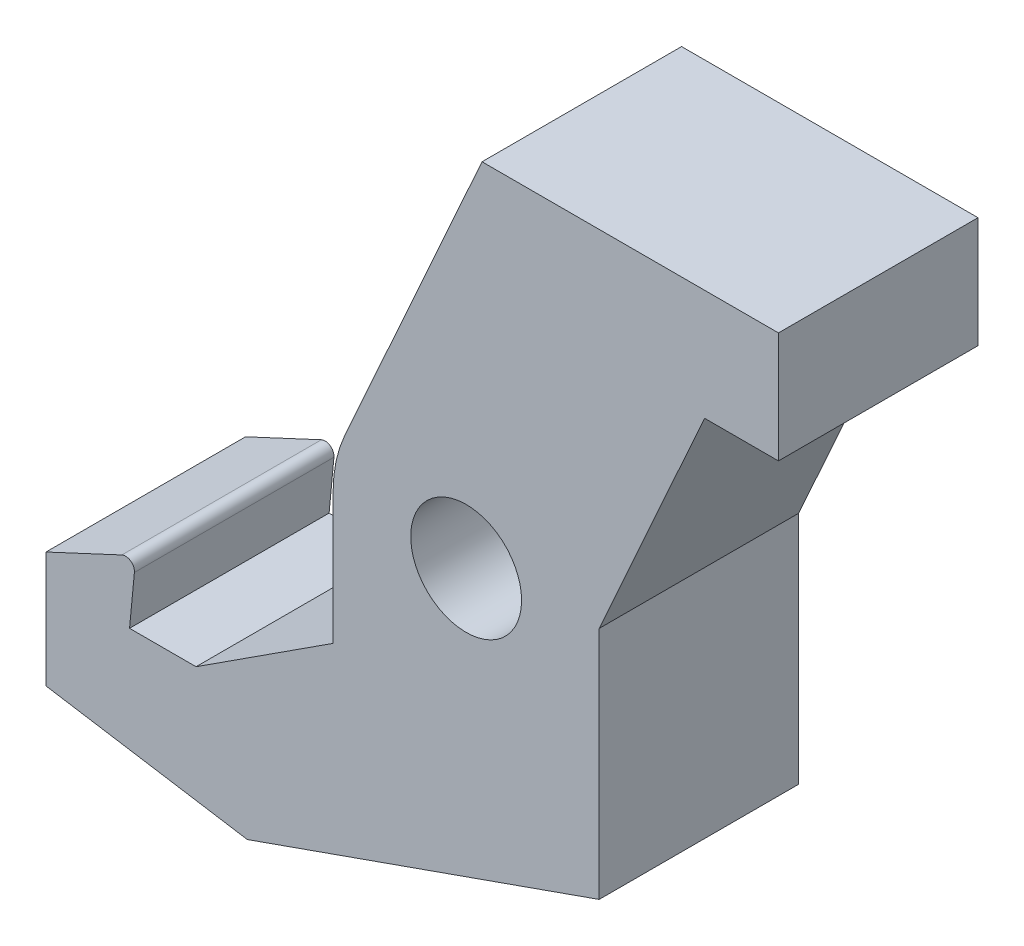
SolidWorks part; units mm, degrees
ref_plane "정면" through (0, 0, 0) normal (0, 0, 1) x (1, 0, 0)
ref_plane "윗면" through (0, 0, 0) normal (0, 1, 0) x (1, 0, 0)
ref_plane "우측면" through (0, 0, 0) normal (1, 0, 0) x (0, 0, -1)
sketch "스케치1" plane through (0, 0, 0) normal (0, 0, 1) x (1, 0, 0)
  line L0 (-6, 0) -> (-6, -5.9283)
  line L1 (-6, -5.9283) -> (-12.1815, -9.9309)
  line L2 (-12.1815, -9.9309) -> (-15.1815, -9.9309)
  line L3 (-15.1815, -9.9309) -> (-14.9625, -7.6405)
  line L4 (-15.5297, -7.2399) -> (-18.9497, -8.834)
  line L5 (-18.9497, -8.834) -> (-18.9497, -12.4044)
  line L6 (6, -9.9309) -> (-9.8715, -15.5268)
  line L7 (6, 0.6556) -> (10.7543, 11.242)
  line L8 (6, -9.9309) -> (6, 0.6556)
  line L9 (10.7543, 11.242) -> (14.0864, 11.242)
  line L10 (14.0864, 11.242) -> (14.0864, 16.242)
  line L11 (14.0864, 16.242) -> (0.7169, 16.242)
  line L12 (0.7169, 16.242) -> (-5.4734, 2.4581)
  line L13 (-9.8715, -15.5268) -> (-18.9497, -14.0674)
  line L14 (-18.9497, -14.0674) -> (-18.9497, -12.4044)
  circle A0 centre (0, 0) radius 2.5
  arc A1 (-5.4734, 2.4581) -> (-6, 0) centre (0, 0) ccw
  arc A2 (-14.9625, -7.6405) -> (-15.5297, -7.2399) centre (-15.3607, -7.6024) ccw
  point P21 (-14.896, -6.9445)
  dimension "D1" = 5
  dimension "D2" = 12
  dimension "D9" = 0.4
  dimension "D3" = 3
  dimension "D4" = 3
  dimension "D8" = 5
extrude "보스-돌출1" add sketch "스케치1" along normal blind 9
